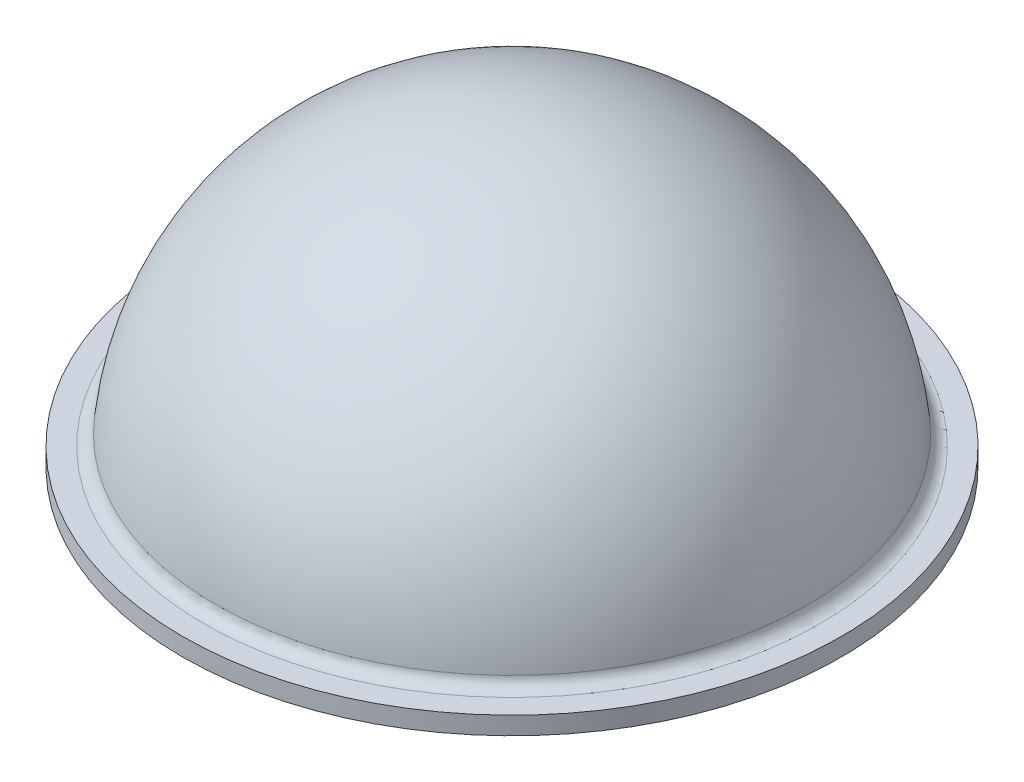
SolidWorks part; units mm, degrees
material "Vidrio"
ref_plane "Alzado" through (0, 0, 0) normal (0, 0, 1) x (1, 0, 0)
ref_plane "Planta" through (0, 0, 0) normal (0, 1, 0) x (1, 0, 0)
ref_plane "Vista lateral" through (0, 0, 0) normal (1, 0, 0) x (0, 0, -1)
sketch "Croquis1" plane through (0, 0, 0) normal (0, 0, 1) x (1, 0, 0)
  line L0 (49.9099, 0) -> (55.4099, 0)
  line L1 (55.4099, 0) -> (55.4099, 3)
  line L2 (55.4099, 3) -> (51.7591, 3)
  line L3 (-47, 0) -> (-71.7245, 0) construction
  line L4 (0, 0) -> (0, 64.4596) construction
  line L5 (0, 50) -> (0, 47)
  arc A0 (46.9153, 2.82) -> (0, 47) centre (0, 0) ccw
  arc A1 (49.7683, 4.8077) -> (0, 50) centre (0, 0) ccw
  arc A2 (49.7683, 4.8077) -> (51.7591, 3) centre (51.7591, 5) ccw
  arc A3 (49.9099, 0) -> (46.9153, 2.82) centre (49.9099, 3) cw
  point P15 (49.9099, 3)
  point P18 (47, 0)
  dimension "D1" = 50
  dimension "D2" = 3
  dimension "D5" = 2
  dimension "D6" = 3
  dimension "D3" = 3
  dimension "D4" = 5.5
revolve "Revolución1" add sketch "Croquis1" angle 360 about L4
